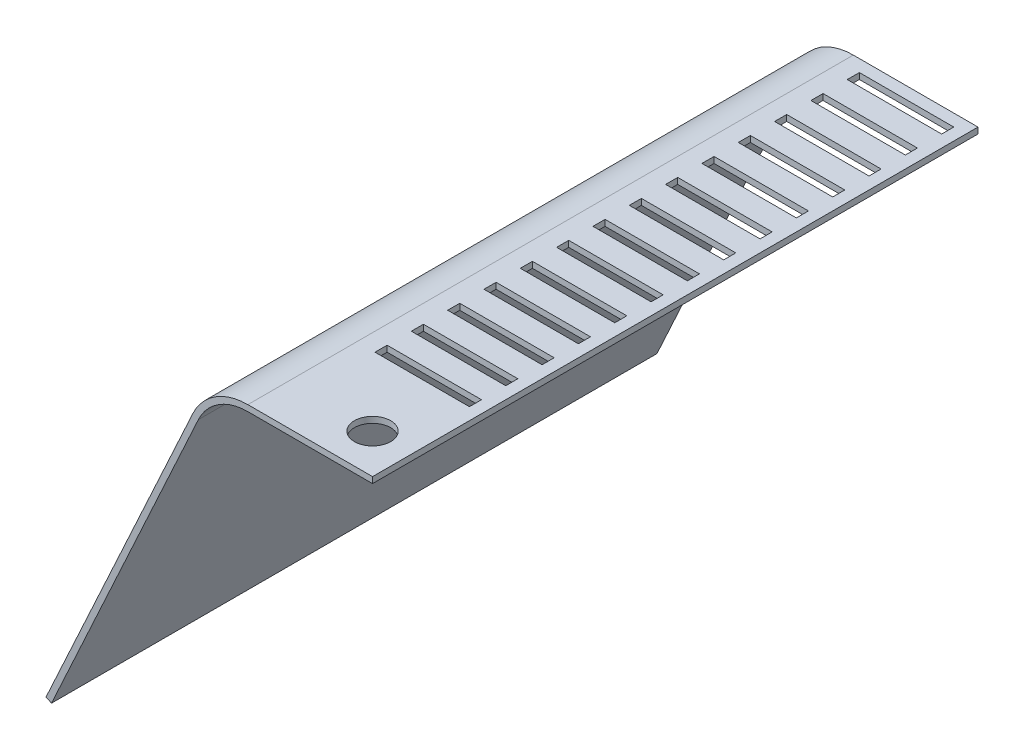
SolidWorks part; units mm, degrees
ref_plane "Front Plane" through (0, 0, 0) normal (0, 0, 1) x (1, 0, 0)
ref_plane "Top Plane" through (0, 0, 0) normal (0, 1, 0) x (1, 0, 0)
ref_plane "Right Plane" through (0, 0, 0) normal (1, 0, 0) x (0, 0, -1)
sketch "Sketch1" plane through (0, 0, 0) normal (0, 0, 1) x (1, 0, 0)
  line L0 (0, 0) -> (-205.95, 0)
  line L1 (-296.7862, -58.1816) -> (-539.333, -585.0317)
  arc A0 (-205.95, 0) -> (-296.7862, -58.1816) centre (-205.95, -100) ccw
  point P6 (-174.7332, -100)
  dimension "D1" = 100
  dimension "D3" = 114.72
  dimension "D2" = 205.95
  dimension "D4" = 580
extrude "Extrude-Thin1" add sketch "Sketch1" along normal mid plane 1000 thin thin type one direction reverse wall 10
sketch "Sketch2" plane through (0, 0, 0) normal (0, 1, 0) x (1, 0, 0)
  line L0 (0, -500) -> (0, 500) construction
  line L1 (-20, 480) -> (-175.95, 480)
  line L2 (-20, 480) -> (-20, 460)
  line L3 (-20, 460) -> (-175.95, 460)
  line L4 (-175.95, 480) -> (-175.95, 460)
  line L5 (0, 500) -> (-205.95, 500) construction
  line L6 (-205.95, -500) -> (-205.95, 500) construction
  dimension "D1" = 20
  dimension "D2" = 20
  dimension "D3" = 20
  dimension "D4" = 30
extrude "Cut-Extrude1" cut sketch "Sketch2" against normal through all
pattern_linear "LPattern1" count 14 spacing 60 along (0, 0, 1) of "Cut-Extrude1"
sketch "Sketch3" plane through (0, 0, 0) normal (0, 1, 0) x (1, 0, 0)
  line L0 (0, -500) -> (-205.95, -500) construction
  line L1 (0, -500) -> (0, 500) construction
  circle A0 centre (-65, -435) radius 30
  dimension "D3" = 60
  dimension "D1" = 65
  dimension "D2" = 65
extrude "Cut-Extrude2" cut sketch "Sketch3" against normal through all
